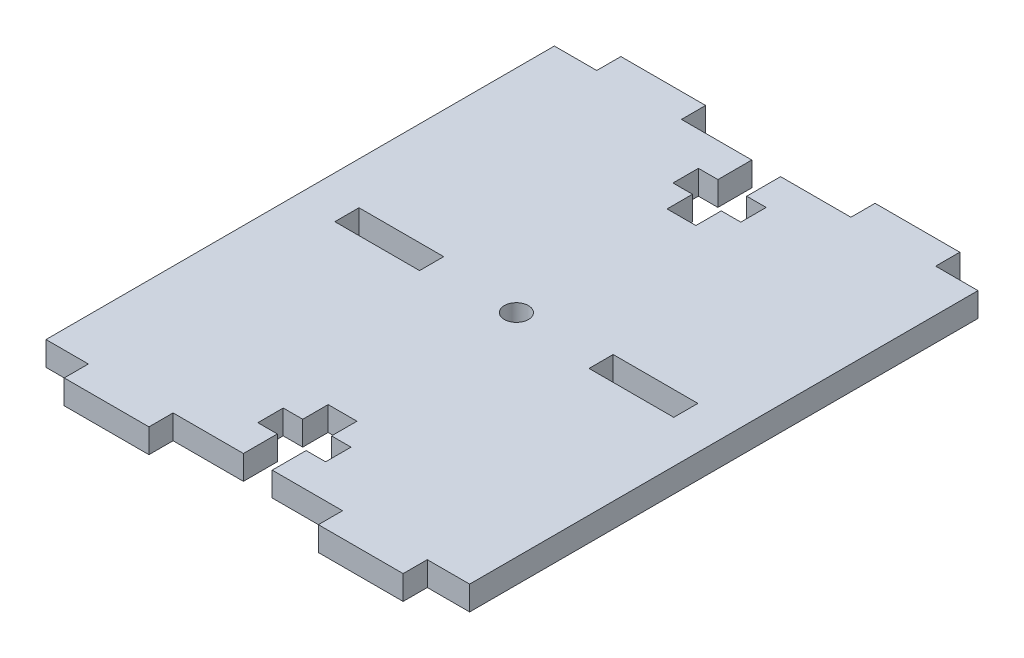
SolidWorks part; units mm, degrees
material "Pine"
ref_plane "Front" through (0, 0, 0) normal (0, 0, 1) x (1, 0, 0)
ref_plane "Top" through (0, 0, 0) normal (0, 1, 0) x (1, 0, 0)
ref_plane "Right" through (0, 0, 0) normal (1, 0, 0) x (0, 0, -1)
sketch "Sketch1" plane through (0, 0, 0) normal (0, 1, 0) x (1, 0, 0)
  line L1 (-25, 30) -> (25, 30)
  line L2 (-25, 30) -> (-25, -30)
  line L3 (-25, -30) -> (25, -30)
  line L4 (25, 30) -> (25, -30)
  line L5 (-25, 30) -> (25, -30) construction
  line L6 (-25, -30) -> (25, 30) construction
  point P0 (0, 0)
  dimension "D1" = 50
  dimension "D2" = 60
extrude "Boss-Extrude1" add sketch "Sketch1" along normal blind 2.85
sketch "Sketch2" plane through (0, 2.85, 0) normal (0, 1, 0) x (1, 0, 0)
  line L0 (25, 30) -> (-25, 30) construction
  line L1 (-20, 30) -> (-10, 30)
  line L2 (-20, 30) -> (-20, 32.85)
  line L3 (-20, 32.85) -> (-10, 32.85)
  line L4 (-10, 30) -> (-10, 32.85)
  line L5 (-20, 30) -> (-25, 30) construction
  line L6 (10, 30) -> (20, 30)
  line L7 (10, 30) -> (10, 32.85)
  line L8 (10, 32.85) -> (20, 32.85)
  line L9 (20, 30) -> (20, 32.85)
  line L10 (20, 30) -> (25, 30) construction
  line L11 (-25, 30) -> (-25, -30) construction
  dimension "D1" = 2.85
  dimension "D2" = 10
  dimension "D3" = 5
extrude "Boss-Extrude2" add sketch "Sketch2" against normal blind 2.85
sketch "Sketch3" plane through (0, 2.85, 0) normal (0, 1, 0) x (1, 0, 0)
  line L0 (-4, 26) -> (-1.7, 26)
  line L1 (-4, 26) -> (-4, 23)
  line L2 (-4, 23) -> (-1.7, 23)
  line L3 (4, 26) -> (4, 23)
  line L4 (-1.7, 20) -> (1.7, 20)
  line L5 (-1.7, 20) -> (-1.7, 23)
  line L6 (-1.7, 30) -> (1.7, 30)
  line L7 (1.7, 20) -> (1.7, 23)
  line L8 (-1.7, 26) -> (-1.7, 30)
  line L9 (1.7, 26) -> (4, 26)
  line L10 (1.7, 26) -> (1.7, 30)
  line L11 (1.7, 23) -> (4, 23)
  line L12 (10, 30) -> (-10, 30) construction
  line L13 (0, 0) -> (0, 20) construction
  point P4 (1.2247, 24.867)
  dimension "D1" = 3.4
  dimension "D2" = 3
  dimension "D3" = 8
  dimension "D4" = 10
  dimension "D5" = 3
extrude "Cut-Extrude1" cut sketch "Sketch3" against normal through all
mirror "Mirror1" about plane through (0, 0, 0) normal (0, 0, 1) of "Boss-Extrude2", "Cut-Extrude1"
sketch "Sketch4" plane through (0, 2.85, 0) normal (0, 1, 0) x (1, 0, 0)
  line L0 (0, 0.515) -> (-10, 0.515) construction
  line L1 (-20, 1.94) -> (-10, 1.94)
  line L2 (-20, 1.94) -> (-20, -0.91)
  line L3 (-20, -0.91) -> (-10, -0.91)
  line L4 (-10, 1.94) -> (-10, -0.91)
  line L5 (10, 1.94) -> (20, 1.94)
  line L6 (10, 1.94) -> (10, -0.91)
  line L7 (10, -0.91) -> (20, -0.91)
  line L8 (20, 1.94) -> (20, -0.91)
  line L9 (0, 0.515) -> (10, 0.515) construction
  line L10 (-25, 30) -> (-25, -30) construction
  line L11 (-25, -30) -> (-20, -30) construction
  circle A0 centre (0, 0.515) radius 1.425
  dimension "D4" = 2.85
  dimension "D1" = 2.85
  dimension "D2" = 10
  dimension "D3" = 5
  dimension "D5" = 29.09
extrude "Cut-Extrude2" cut sketch "Sketch4" against normal through all
